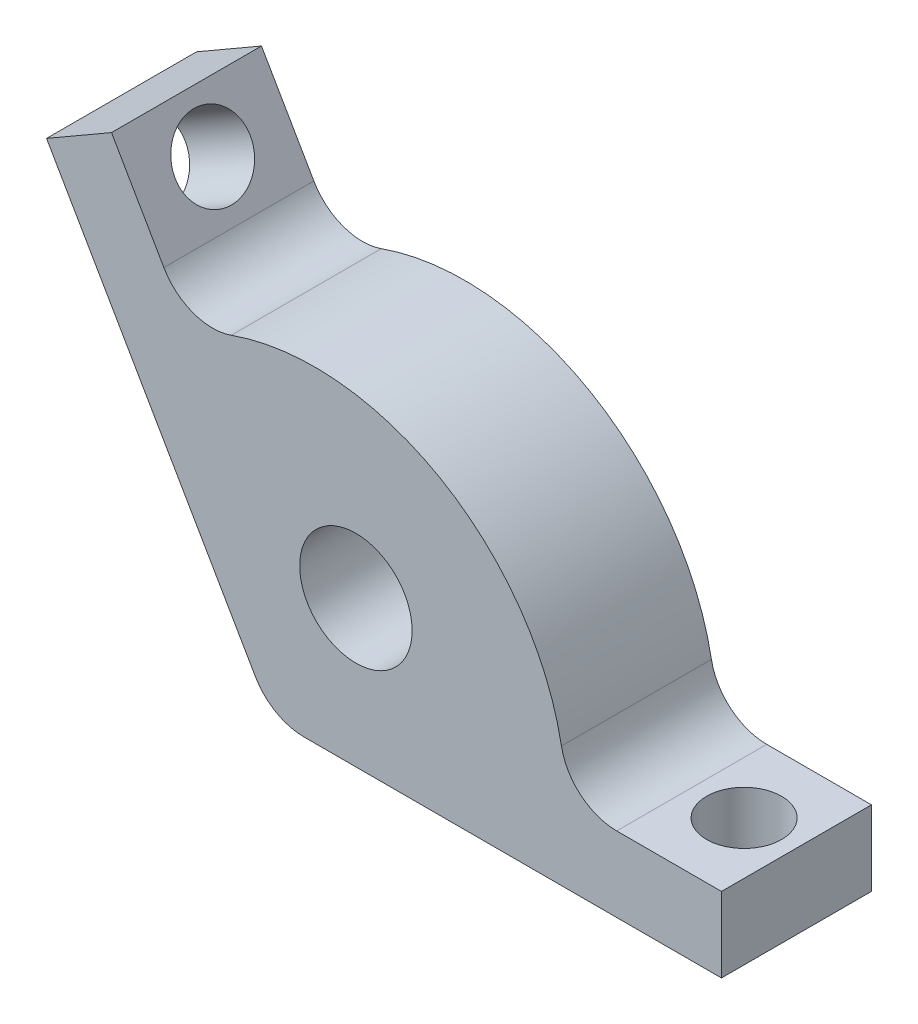
SolidWorks part; units mm, degrees
material "AISI 304"
ref_plane "Front" through (0, 0, 0) normal (0, 0, 1) x (1, 0, 0)
ref_plane "Top" through (0, 0, 0) normal (0, 1, 0) x (1, 0, 0)
ref_plane "Right" through (0, 0, 0) normal (1, 0, 0) x (0, 0, -1)
sketch "Sketch1" plane through (0, 0, 0) normal (0, 0, 1) x (1, 0, 0)
  line L0 (0, 0) -> (19.05, 0)
  line L1 (0, 0) -> (-9.525, 16.4978)
  line L2 (-9.525, 16.4978) -> (-6.7754, 18.0853)
  line L3 (-6.7754, 18.0853) -> (-3.4776, 12.3733)
  line L4 (19.05, 0) -> (19.05, 3.175)
  line L5 (19.05, 3.175) -> (12.4544, 3.175)
  line L6 (0, 0) -> (7.1437, 12.3733) construction
  arc A0 (-3.4776, 12.3733) -> (12.4544, 3.175) centre (1.8331, 3.175) cw
  circle A1 centre (3.5719, 6.1867) radius 2.3813
  point P12 (10.2019, 10.3049)
  point P13 (0, 0)
  point P14 (7.1437, 12.3733)
  point P15 (3.6651, 6.3481)
  dimension "D4" = 4.7625
  dimension "D1" = 19.05
  dimension "D2" = 3.175
  dimension "D3" = 120
  dimension "D5" = 7.1437
extrude "Boss-Extrude1" add sketch "Sketch1" along normal blind 6.35
fillet "Fillet1" radius 2.3812 3 edges at (0, 0, 3.175) (12.4544, 3.175, 3.175) (-3.4776, 12.3733, 3.175)
sketch "Sketch2" plane through (0, 3.175, 0) normal (0, 1, 0) x (1, 0, 0)
  line L0 (19.05, -6.35) -> (19.05, 0) construction
  line L1 (19.05, 0) -> (14.6158, 0) construction
  circle A0 centre (16.8329, -3.175) radius 1.5875
  point P4 (19.05, -3.175)
  point P7 (16.8329, 0)
  dimension "D1" = 3.175
extrude "Cut-Extrude1" cut sketch "Sketch2" against normal through all
ref_axis "Axis1" through (0, 0, -80.9) along (0, 0, 1)
pattern_circular "CirPattern1" count 3 over 360 about axis through (0, 0, -80.9) along (0, 0, 1) of "Cut-Extrude1"
